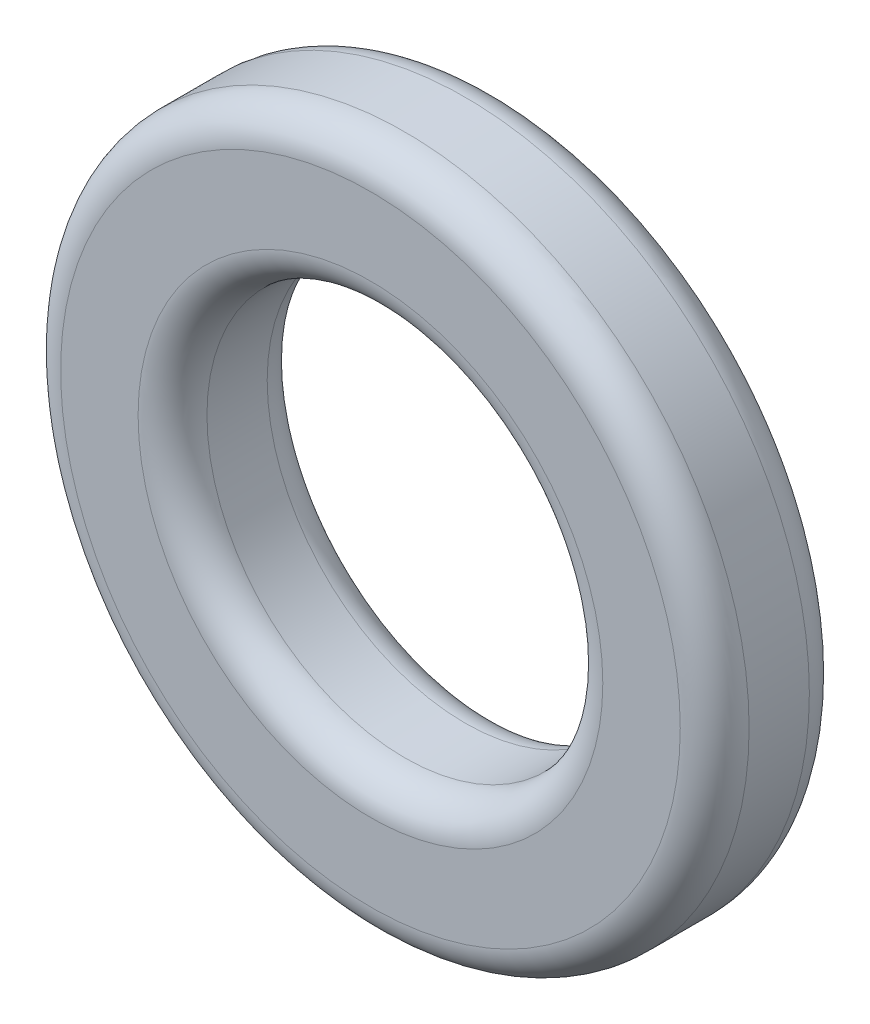
SolidWorks part; units mm, degrees
ref_plane "Front Plane" through (0, 0, 0) normal (0, 0, 1) x (1, 0, 0)
ref_plane "Top Plane" through (0, 0, 0) normal (0, 1, 0) x (1, 0, 0)
ref_plane "Right Plane" through (0, 0, 0) normal (1, 0, 0) x (0, 0, -1)
sketch "Sketch2" plane through (0, 0, 0) normal (0, 0, 1) x (1, 0, 0)
  circle A0 centre (0, 0) radius 4
  circle A1 centre (0, 0) radius 2.3
extrude "Boss-Extrude1" add sketch "Sketch2" along normal blind 1.5
fillet "Fillet1" radius 0.4 4 edges at (2.3, 0, 0) (4, 0, 0) (2.3, 0, 1.5) (4, 0, 1.5)
